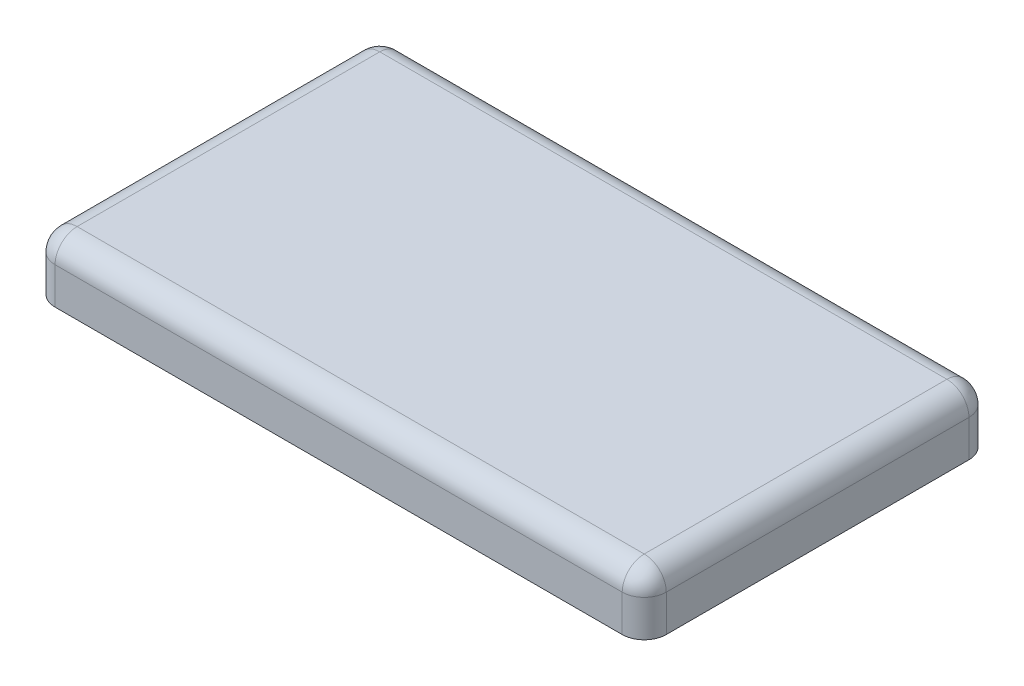
SolidWorks part; units mm, degrees
ref_plane "Front Plane" through (0, 0, 0) normal (0, 0, 1) x (1, 0, 0)
ref_plane "Top Plane" through (0, 0, 0) normal (0, 1, 0) x (1, 0, 0)
ref_plane "Right Plane" through (0, 0, 0) normal (1, 0, 0) x (0, 0, -1)
sketch "Sketch1" plane through (0, 0, 0) normal (0, 1, 0) x (1, 0, 0)
  line L1 (0, 0) -> (41.6, 0)
  line L2 (0, 0) -> (0, 23.6)
  line L3 (0, 23.6) -> (41.6, 23.6)
  line L4 (41.6, 0) -> (41.6, 23.6)
  dimension "D1" = 41.6
  dimension "D2" = 23.6
extrude "Boss-Extrude1" add sketch "Sketch1" along normal blind 4
sketch "Sketch2" plane through (0, 0, 0) normal (0, -1, 0) x (1, 0, 0)
  line L0 (20.8, 0) -> (20.8, -23.6) construction
  line L1 (0, 0) -> (41.6, 0) construction
  line L2 (41.6, -23.6) -> (0, -23.6) construction
  line L4 (1.3, -22.3) -> (40.3, -22.3)
  line L5 (1.3, -22.3) -> (1.3, -1.3)
  line L6 (1.3, -1.3) -> (40.3, -1.3)
  line L7 (40.3, -22.3) -> (40.3, -1.3)
  line L8 (1.3, -22.3) -> (40.3, -1.3) construction
  line L9 (1.3, -1.3) -> (40.3, -22.3) construction
  line L10 (0, -23.6) -> (41.6, -23.6) construction
  line L11 (0, -23.6) -> (0, 0) construction
  line L12 (0, 0) -> (41.6, 0) construction
  line L13 (41.6, -23.6) -> (41.6, 0) construction
  line L14 (0, -23.6) -> (41.6, 0) construction
  line L15 (0, 0) -> (41.6, -23.6) construction
  point P6 (20.8, -11.8)
  point P11 (20.8, -11.8)
  dimension "D1" = 1.3
  dimension "D2" = 1.3
extrude "Cut-Extrude1" cut sketch "Sketch2" against normal blind 2.6
fillet "Fillet1" radius 1.5 8 edges at (20.8, 4, -23.6) (41.6, 4, -11.8) (20.8, 4, 0) (0, 4, -11.8) (0, 2, 0) (0, 2, -23.6) (41.6, 2, -23.6) (41.6, 2, 0)
